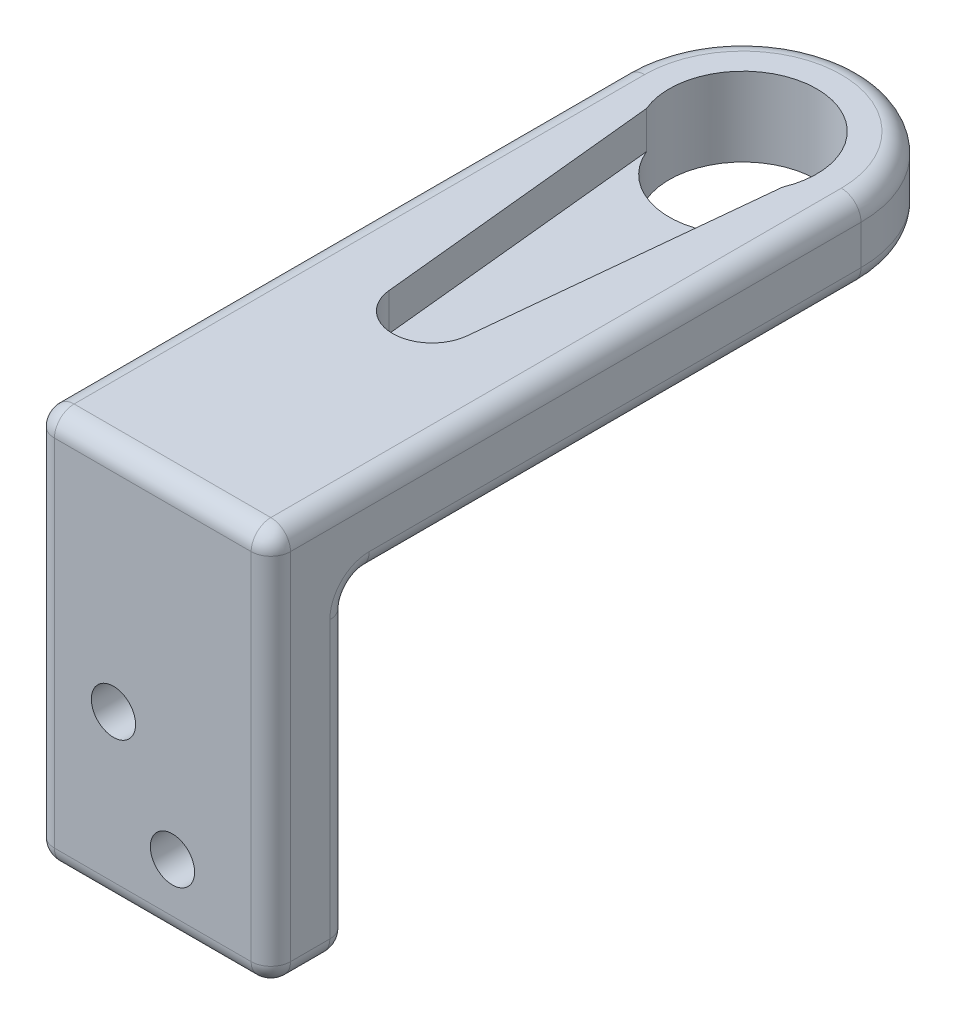
SolidWorks part; units mm, degrees
ref_plane "Front Plane" through (0, 0, 0) normal (0, 0, 1) x (1, 0, 0)
ref_plane "Top Plane" through (0, 0, 0) normal (0, 1, 0) x (1, 0, 0)
ref_plane "Right Plane" through (0, 0, 0) normal (1, 0, 0) x (0, 0, -1)
sketch "Sketch1" plane through (0, 0, 0) normal (0, 1, 0) x (1, 0, 0)
  line L1 (-6, 0) -> (0, 0) construction
  line L4 (-6, 0) -> (-6, -30)
  line L5 (-6, -30) -> (6, -30)
  line L6 (6, -30) -> (6, 0)
  arc A1 (-6, 0) -> (6, 0) centre (0, 0) cw
  dimension "D3" = 6
  dimension "D1" = 6
  dimension "D2" = 30
extrude "Pitch Arm Base" add sketch "Sketch1" along normal blind 4
sketch "Sketch2" plane through (0, 4, 0) normal (0, 1, 0) x (1, 0, 0)
  circle A0 centre (0, 0) radius 3.75
  dimension "D1" = 7.5
extrude "Pitch Arm Mounting Hole" cut sketch "Sketch2" against normal up to next
sketch "Sketch4" plane through (0, 4, 0) normal (0, 1, 0) x (1, 0, 0)
  line L0 (-3.46, -1.446) -> (-1.9899, -16.006)
  line L1 (3.46, -1.446) -> (1.9899, -16.006)
  line L4 (-6, 0) -> (-6, -30) construction
  line L5 (0, -15.8051) -> (0, 0) construction
  arc A0 (-1.9899, -16.006) -> (1.9899, -16.006) centre (0, -15.8051) ccw
  arc A1 (-3.46, -1.446) -> (3.46, -1.446) centre (0, 0) ccw
  circle A2 centre (0, 0) radius 3.75 construction
  dimension "D3" = 2
  dimension "D1" = 14.56
  dimension "D2" = 2.54
extrude "Pitch Arm Slot" cut sketch "Sketch4" against normal blind 1.9
sketch "Sketch5" plane through (0, 0, 0) normal (0, -1, 0) x (1, 0, 0)
  line L1 (-6, 30) -> (6, 30)
  line L2 (-6, 30) -> (-6, 26)
  line L3 (-6, 26) -> (6, 26)
  line L4 (6, 30) -> (6, 26)
  dimension "D1" = 4
extrude "Mounting Bracket" add sketch "Sketch5" along normal blind 16.05
sketch "Sketch8" plane through (0, 0, 26) normal (0, 0, -1) x (-1, 0, 0)
  line L4 (6, -16.05) -> (-6, -16.05) construction
  line L7 (-6, -16.05) -> (-6, 0) construction
  circle A0 centre (-1, -12.55) radius 1.125
  circle A1 centre (2, -7.55) radius 1.125
  dimension "D1" = 2.25
  dimension "D2" = 2.25
  dimension "D3" = 5
  dimension "D4" = 3.5
  dimension "D5" = 5
  dimension "D6" = 3
extrude "Bracket Mounting Holes" cut sketch "Sketch8" against normal up to next
fillet "1mm Fillets" radius 1 16 edges at (6, -8.025, 26) (-6, -8.025, 26) (6, 4, 15) (0, 4, -6) (6, 0, 13) (0, 0, -6) (0, 4, 30) (6, -6.025, 30) (-6, -6.025, 30) (0, -16.05, 30) (6, -16.05, 28) (0, -16.05, 26) (-6, -16.05, 28) (-6, 4, 15) (-6, 0, 13) (0, 0, 26)
